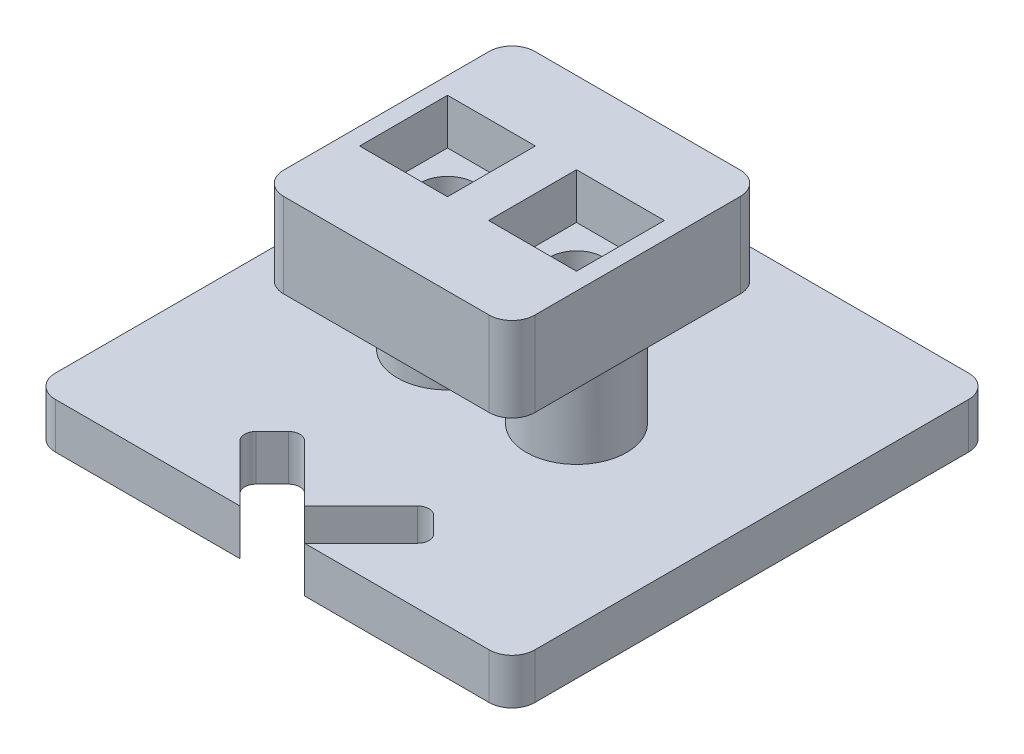
SolidWorks part; units mm, degrees
ref_plane "Front Plane" through (0, 0, 0) normal (0, 0, 1) x (1, 0, 0)
ref_plane "Top Plane" through (0, 0, 0) normal (0, 1, 0) x (1, 0, 0)
ref_plane "Right Plane" through (0, 0, 0) normal (1, 0, 0) x (0, 0, -1)
sketch "Sketch1" plane through (0, 0, 0) normal (0, 1, 0) x (1, 0, 0)
  line L1 (-5.5, -5.5) -> (5.5, -5.5)
  line L2 (-5.5, -5.5) -> (-5.5, 5.5)
  line L3 (-5.5, 5.5) -> (5.5, 5.5)
  line L4 (5.5, -5.5) -> (5.5, 5.5)
  line L5 (-5.5, -5.5) -> (5.5, 5.5) construction
  line L6 (-5.5, 5.5) -> (5.5, -5.5) construction
  point P0 (0, 0)
  dimension "D1" = 11
  dimension "D2" = 11
extrude "Boss-Extrude1" add sketch "Sketch1" along normal blind 3.7
fillet "Fillet1" radius 1 4 edges at (-5.5, 1.85, -5.5) (-5.5, 1.85, 5.5) (5.5, 1.85, -5.5) (5.5, 1.85, 5.5)
sketch "Sketch2" plane through (0, 3.7, 0) normal (0, 1, 0) x (1, 0, 0)
  line L0 (-2.825, 0) -> (2.825, 0) construction
  line L2 (-4.75, -1.925) -> (-0.9, -1.925)
  line L3 (-4.75, -1.925) -> (-4.75, 1.925)
  line L4 (-4.75, 1.925) -> (-0.9, 1.925)
  line L5 (-0.9, -1.925) -> (-0.9, 1.925)
  line L6 (-4.75, -1.925) -> (-0.9, 1.925) construction
  line L7 (-4.75, 1.925) -> (-0.9, -1.925) construction
  line L8 (0.9, -1.925) -> (4.75, -1.925)
  line L9 (0.9, -1.925) -> (0.9, 1.925)
  line L10 (0.9, 1.925) -> (4.75, 1.925)
  line L11 (4.75, -1.925) -> (4.75, 1.925)
  line L12 (0.9, -1.925) -> (4.75, 1.925) construction
  line L13 (0.9, 1.925) -> (4.75, -1.925) construction
  point P4 (0, 0)
  dimension "D1" = 3.85
  dimension "D2" = 3.85
  dimension "D3" = 3.85
  dimension "D4" = 3.85
  dimension "D5" = 5.65
extrude "Cut-Extrude1" cut sketch "Sketch2" against normal blind 2
sketch "Sketch4" plane through (0, 0, 0) normal (0, -1, 0) x (-1, 0, 0)
  line L0 (2.825, 0) -> (-2.825, 0) construction
  circle A0 centre (2.825, 0) radius 2.2
  circle A1 centre (-2.825, 0) radius 2.2
  point P4 (0, 0)
  point P8 (0, 0)
  dimension "D1" = 5.65
  dimension "D2" = 4.4
  dimension "D3" = 4.4
extrude "Boss-Extrude2" add sketch "Sketch4" along normal blind 6
sketch "Sketch5" plane through (0, -6, 0) normal (0, -1, 0) x (-1, 0, 0)
  line L1 (9.5, 10.5) -> (-9.5, 10.5)
  line L2 (10.5, 9.5) -> (10.5, -9.5)
  line L3 (9.5, -10.5) -> (-9.5, -10.5)
  line L4 (-10.5, 9.5) -> (-10.5, -9.5)
  line L5 (10.5, 10.5) -> (-10.5, -10.5) construction
  line L6 (10.5, -10.5) -> (-10.5, 10.5) construction
  arc A0 (10.5, -9.5) -> (9.5, -10.5) centre (9.5, -9.5) cw
  arc A1 (-10.5, -9.5) -> (-9.5, -10.5) centre (-9.5, -9.5) ccw
  arc A2 (-9.5, 10.5) -> (-10.5, 9.5) centre (-9.5, 9.5) ccw
  arc A3 (9.5, 10.5) -> (10.5, 9.5) centre (9.5, 9.5) cw
  point P0 (0, 0)
  dimension "D3" = 1
  dimension "D1" = 21
  dimension "D2" = 21
extrude "Boss-Extrude3" add sketch "Sketch5" against normal blind 2
sketch "Sketch3" plane through (0, 3.7, 0) normal (0, 1, 0) x (1, 0, 0)
  line L0 (-2.825, 0) -> (2.825, 0) construction
  circle A0 centre (-2.825, 0) radius 1.2
  circle A1 centre (2.825, 0) radius 1.2
  point P4 (0, 0)
  point P5 (0, 0)
  point P8 (0, 0)
  dimension "D2" = 2.4
  dimension "D3" = 2.4
  dimension "D1" = 5.65
extrude "Cut-Extrude2" cut sketch "Sketch3" against normal through all
sketch "Sketch7" plane through (0, -4, 0) normal (0, 1, 0) x (1, 0, 0)
  line L0 (9.5, -10.5) -> (-9.5, -10.5) construction
  line L1 (2.8284, -14.7426) -> (4.2426, -13.3284)
  line L2 (2.8284, -14.7426) -> (-3.8891, -8.0251)
  line L3 (-3.8891, -7.318) -> (-3.182, -6.6109)
  line L4 (4.2426, -13.3284) -> (-2.4749, -6.6109)
  line L5 (2.8284, -14.7426) -> (-2.8284, -6.2574) construction
  line L6 (-4.2426, -7.6716) -> (4.2426, -13.3284) construction
  line L8 (-4.2426, -13.3284) -> (-2.8284, -14.7426)
  line L9 (-4.2426, -13.3284) -> (2.4749, -6.6109)
  line L10 (3.182, -6.6109) -> (3.8891, -7.318)
  line L11 (-2.8284, -14.7426) -> (3.8891, -8.0251)
  line L12 (-4.2426, -13.3284) -> (4.2426, -7.6716) construction
  line L13 (2.8284, -6.2574) -> (-2.8284, -14.7426) construction
  arc A0 (-2.4749, -6.6109) -> (-3.182, -6.6109) centre (-2.8284, -6.9645) ccw
  arc A1 (3.8891, -7.318) -> (3.8891, -8.0251) centre (3.5355, -7.6716) cw
  arc A2 (3.182, -6.6109) -> (2.4749, -6.6109) centre (2.8284, -6.9645) ccw
  arc A3 (-3.8891, -7.318) -> (-3.8891, -8.0251) centre (-3.5355, -7.6716) ccw
  point P0 (0, -10.5)
  point P7 (0, -10.5)
  point P12 (-1.4142, -10.5)
  point P13 (1.4142, -10.5)
  line M12 (-9.5, -10.5) -> (9.5, -10.5)
  dimension "D7" = 0.5
  dimension "D8" = 0.5
  dimension "D1" = 2
  dimension "D2" = 45
  dimension "D3" = 2
  dimension "D4" = 45
  dimension "D5" = 4
  dimension "D6" = 4
extrude "Cut-Extrude3" cut sketch "Sketch7" against normal through all contours L10 A2 L9 L4 L11 A1 | L3 A3 L2 L9 L4 A0 | L9 L4 M12
equation "\"D2@Sketch2\"=\"D1@Sketch2\""
equation "\"D3@Sketch2\"=\"D1@Sketch2\""
equation "\"D4@Sketch2\"=\"D1@Sketch2\""
equation "\"D2@Sketch1\"=\"D1@Sketch1\""
equation "\"D3@Sketch3\"=\"D2@Sketch3\""
equation "\"D3@Sketch4\"=\"D2@Sketch4\""
equation "\"D2@Sketch5\"=\"D1@Sketch5\""
equation "\"D3@Sketch7\"=\"D1@Sketch7\""
equation "\"D6@Sketch7\"=\"D5@Sketch7\""
